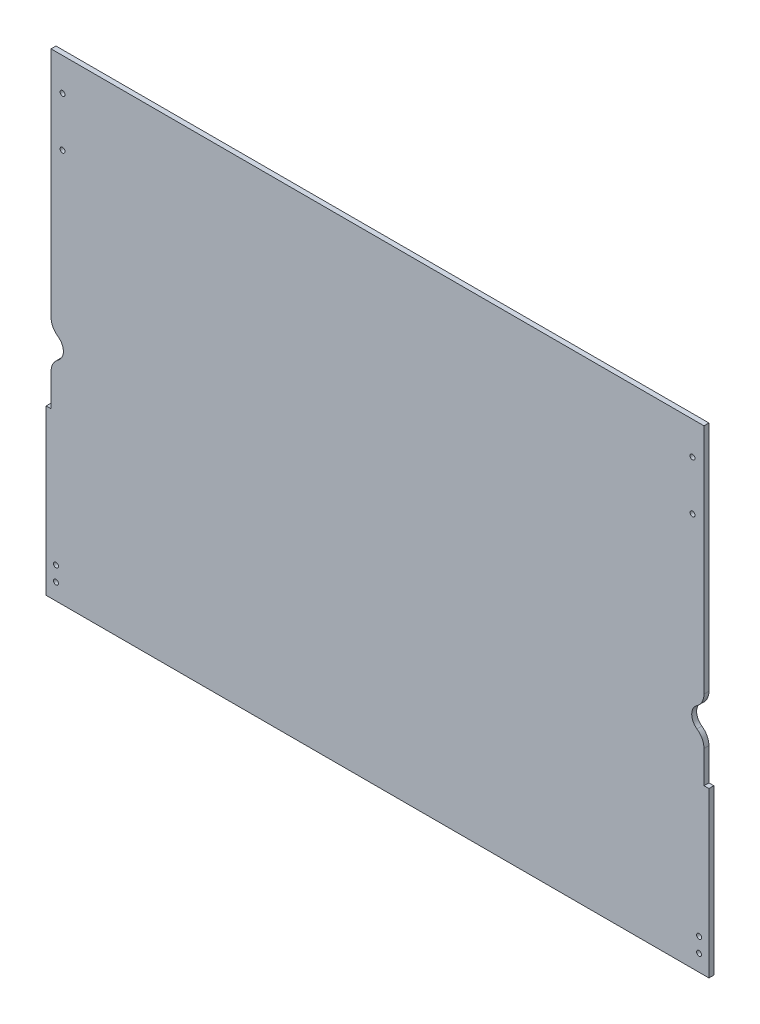
SolidWorks part; units mm, degrees
material "ABS PC"
ref_plane "前视基准面" through (0, 0, 0) normal (0, 0, 1) x (1, 0, 0)
ref_plane "上视基准面" through (0, 0, 0) normal (0, 1, 0) x (1, 0, 0)
ref_plane "右视基准面" through (0, 0, 0) normal (1, 0, 0) x (0, 0, -1)
sketch "草图1" plane through (0, 0, 0) normal (0, 0, 1) x (1, 0, 0)
  line L0 (0, 0) -> (0, 323.0724) construction
  line L1 (199, 290) -> (-199, 290)
  line L2 (-199, 290) -> (-199, 100)
  line L3 (199, 290) -> (199, 100)
  line L4 (-199, 100) -> (-202, 100)
  line L5 (199, 100) -> (202, 100)
  line L6 (-202, 100) -> (-202, 0)
  line L7 (202, 100) -> (202, 0)
  line L8 (-202, 0) -> (202, 0)
  point P6 (0, 290)
  dimension "D1" = 398
  dimension "D2" = 290
  dimension "D3" = 100
  dimension "D4" = 404
extrude "凸台-拉伸1" add sketch "草图1" along normal blind 3
sketch "草图2" plane through (0, 0, 3) normal (0, 0, 1) x (1, 0, 0)
  line L0 (192, 290) -> (192, 0) construction
  line L1 (199, 290) -> (-199, 290) construction
  line L2 (-202, 0) -> (202, 0) construction
  line L3 (0, 290) -> (0, 0) construction
  line L4 (199, 100) -> (199, 290) construction
  line L5 (196, 0) -> (196, 290) construction
  line L6 (202, 0) -> (202, 100) construction
  circle A0 centre (192, 270) radius 1.5
  circle A1 centre (192, 240) radius 1.5
  circle A2 centre (-192, 240) radius 1.5
  circle A3 centre (-192, 270) radius 1.5
  circle A4 centre (196, 19) radius 1.5
  circle A5 centre (196, 10) radius 1.5
  circle A6 centre (-196, 10) radius 1.5
  circle A7 centre (-196, 19) radius 1.5
  dimension "D2" = 30
  dimension "D4" = 3
  dimension "D6" = 9
  dimension "D7" = 3
  dimension "D1" = 7
  dimension "D3" = 20
  dimension "D5" = 6
  dimension "D8" = 271
extrude "切除-拉伸1" cut sketch "草图2" against normal through all
sketch "草图3" plane through (0, 0, 3) normal (0, 0, 1) x (1, 0, 0)
  line L0 (199, 100) -> (199, 290) construction
  line L2 (-202, 0) -> (202, 0) construction
  line L3 (0, 290) -> (0, 0) construction
  line L4 (199, 290) -> (-199, 290) construction
  circle A0 centre (199, 134) radius 7.5
  circle A1 centre (-199, 134) radius 7.5
  dimension "D1" = 134
  dimension "D2" = 15
extrude "切除-拉伸2" cut sketch "草图3" against normal through all
fillet "圆角1" radius 10 4 edges at (-199, 126.5, 1.5) (-199, 141.5, 1.5) (199, 141.5, 1.5) (199, 126.5, 1.5)
